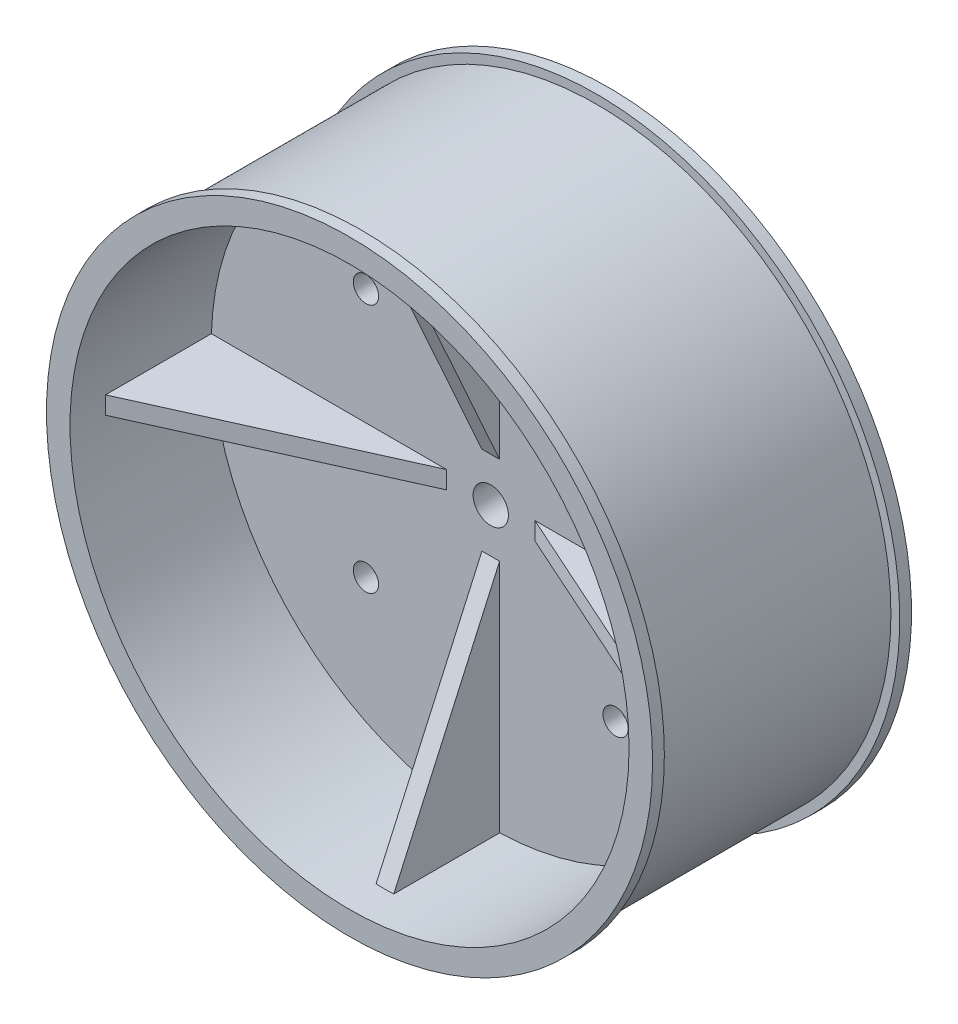
SolidWorks part; units mm, degrees
ref_plane "Front Plane" through (0, 0, 0) normal (0, 0, 1) x (1, 0, 0)
ref_plane "Top Plane" through (0, 0, 0) normal (0, 1, 0) x (1, 0, 0)
ref_plane "Right Plane" through (0, 0, 0) normal (1, 0, 0) x (0, 0, -1)
sketch "Sketch1" plane through (0, 0, 0) normal (0, 0, 1) x (1, 0, 0)
  circle A0 centre (0, 0) radius 50
  circle A1 centre (0, 0) radius 47.5
  dimension "D1" = 100
  dimension "D2" = 2.5
extrude "Boss-Extrude1" add sketch "Sketch1" along normal blind 40
sketch "Sketch2" plane through (0, 0, 40) normal (0, 0, 1) x (1, 0, 0)
  circle A0 centre (0, 0) radius 47.5
  circle A1 centre (0, 0) radius 51.5
  circle A2 centre (0, 0) radius 50 construction
  dimension "D1" = 1.5
  dimension "D2" = 95
extrude "Boss-Extrude2" add sketch "Sketch2" along normal blind 2
sketch "Sketch3" plane through (0, 0, 0) normal (0, 0, -1) x (-1, 0, 0)
  circle A0 centre (0, 0) radius 47.5
  circle A1 centre (0, 0) radius 51.5
  circle A2 centre (0, 0) radius 50 construction
  dimension "D1" = 1.5
  dimension "D2" = 95
extrude "Boss-Extrude3" add sketch "Sketch3" along normal blind 2
ref_plane "Plane1" through (0, 0, 15) normal (0, 0, -1) x (-1, 0, 0)
sketch "Sketch4" plane through (0, 0, 15) normal (0, 0, -1) x (-1, 0, 0)
  circle A0 centre (0, 0) radius 47.5
  dimension "D1" = 95
extrude "Boss-Extrude4" add sketch "Sketch4" against normal blind 3
sketch "Sketch5" plane through (0, 0, 15) normal (0, 0, -1) x (-1, 0, 0)
  circle A0 centre (0, 0) radius 8
  dimension "D1" = 16
extrude "Boss-Extrude5" add sketch "Sketch5" along normal blind 25
sketch "Sketch6" plane through (0, 0, 15) normal (0, 0, -1) x (-1, 0, 0)
  circle A0 centre (0, 0) radius 5
  dimension "D1" = 10
extrude "Boss-Extrude6" add sketch "Sketch6" along normal blind 26.25
sketch "Sketch7" plane through (0, 0, 0) normal (0, 1, 0) x (1, 0, 0)
  line L0 (0, 0) -> (0, -15) construction
  line L1 (56.65, -15) -> (-56.65, -15) construction
  line L2 (-47.5, -15) -> (-5, -15)
  line L3 (-47.5, -15) -> (-47.5, -4)
  line L4 (-47.5, -4) -> (-5, -15)
  line L5 (47.5, -15) -> (47.5, -4)
  line L6 (47.5, -4) -> (5, -15)
  line L7 (5, -15) -> (47.5, -15)
  point P8 (0, -15)
  dimension "D1" = 10
  dimension "D2" = 11
  dimension "D3" = 47.5
extrude "Boss-Extrude7" add sketch "Sketch7" along normal mid plane 3
sketch "Sketch8" plane through (0, 0, 0) normal (1, 0, 0) x (0, 0, -1)
  line L0 (0, 0) -> (-15, 0) construction
  line L1 (-15, -49) -> (-15, 49) construction
  line L2 (-15, -49) -> (-4, -49)
  line L3 (-4, -49) -> (-15, -5)
  line L4 (-15, -5) -> (-15, -49)
  line L5 (-15, 5) -> (-15, 49)
  line L6 (-15, 49) -> (-4, 49)
  line L7 (-4, 49) -> (-15, 5)
  point P6 (-15, 0)
  dimension "D1" = 15
  dimension "D2" = 98
  dimension "D3" = 11
  dimension "D4" = 10
extrude "Boss-Extrude8" add sketch "Sketch8" along normal mid plane 3
sketch "Sketch10" plane through (0, 0, 0) normal (0, 1, 0) x (1, 0, 0)
  line L0 (0, -42) -> (0, -18) construction
  line L1 (-51.5, -42) -> (51.5, -42) construction
  line L2 (-47.5, -18) -> (47.5, -18) construction
  line L3 (-47.5, -18) -> (-47.5, -36)
  line L4 (-47.5, -36) -> (-7.5, -18)
  line L5 (-7.5, -18) -> (-47.5, -18)
  line L6 (7.5, -18) -> (47.5, -18)
  line L7 (47.5, -36) -> (7.5, -18)
  line L8 (47.5, -18) -> (47.5, -36)
  point P8 (0, -18)
  dimension "D1" = 24
  dimension "D2" = 95
  dimension "D3" = 18
  dimension "D4" = 15
extrude "Boss-Extrude9" add sketch "Sketch10" along normal mid plane 3
sketch "Sketch11" plane through (0, 0, 0) normal (1, 0, 0) x (0, 0, -1)
  line L0 (-42, 0) -> (-18, 0) construction
  line L1 (-42, 47.5) -> (-42, -47.5) construction
  line L2 (-18, 47.5) -> (-18, -47.5) construction
  line L3 (-18, 47.5) -> (-36, 47.5)
  line L4 (-36, 47.5) -> (-18, 7.5)
  line L5 (-18, 7.5) -> (-18, 47.5)
  line L6 (-18, -7.5) -> (-18, -47.5)
  line L7 (-36, -47.5) -> (-18, -7.5)
  line L8 (-18, -47.5) -> (-36, -47.5)
  point P8 (-18, 0)
  dimension "D1" = 24
  dimension "D2" = 95
  dimension "D3" = 18
  dimension "D4" = 15
extrude "Boss-Extrude10" add sketch "Sketch11" along normal mid plane 3
sketch "Sketch12" plane through (0, 0, -11.25) normal (0, 0, -1) x (-1, 0, 0)
  circle A0 centre (0, 0) radius 3
  dimension "D1" = 6
extrude "Cut-Extrude1" cut sketch "Sketch12" against normal through all both and the other way through all
sketch "Sketch13" plane through (0, 0, -11.25) normal (0, 0, -1) x (-1, 0, 0)
  circle A0 centre (0, 0) radius 4
  dimension "D1" = 8
extrude "Cut-Extrude2" cut sketch "Sketch13" against normal blind 20
sketch "Sketch14" plane through (0, 0, 0) normal (0, 1, 0) x (1, 0, 0)
  line L0 (51.5, 2) -> (-51.5, 2) construction
  circle A0 centre (0, 3.5) radius 1.5
  dimension "D1" = 3
extrude "Cut-Extrude3" cut sketch "Sketch14" along normal blind 20
sketch "Sketch15" plane through (0, 0, 18) normal (0, 0, 1) x (1, 0, 0)
  line L0 (0, 0) -> (59.2017, 0) construction
  line L1 (0, 0) -> (41.5679, 41.5679) construction
  circle A0 centre (21.2132, 21.2132) radius 2.15
  circle A1 centre (21.2132, -21.2132) radius 2.15
  circle A2 centre (-21.2132, -21.2132) radius 2.15
  circle A3 centre (-21.2132, 21.2132) radius 2.15
  point P15 (0, 0)
  dimension "D2" = 4.3
  dimension "D5" = 30
  dimension "D6" = 42.4264
  dimension "D3" = 30
  dimension "D1" = 45
  dimension "D4" = 4
extrude "Cut-Extrude4" cut sketch "Sketch15" against normal through all
